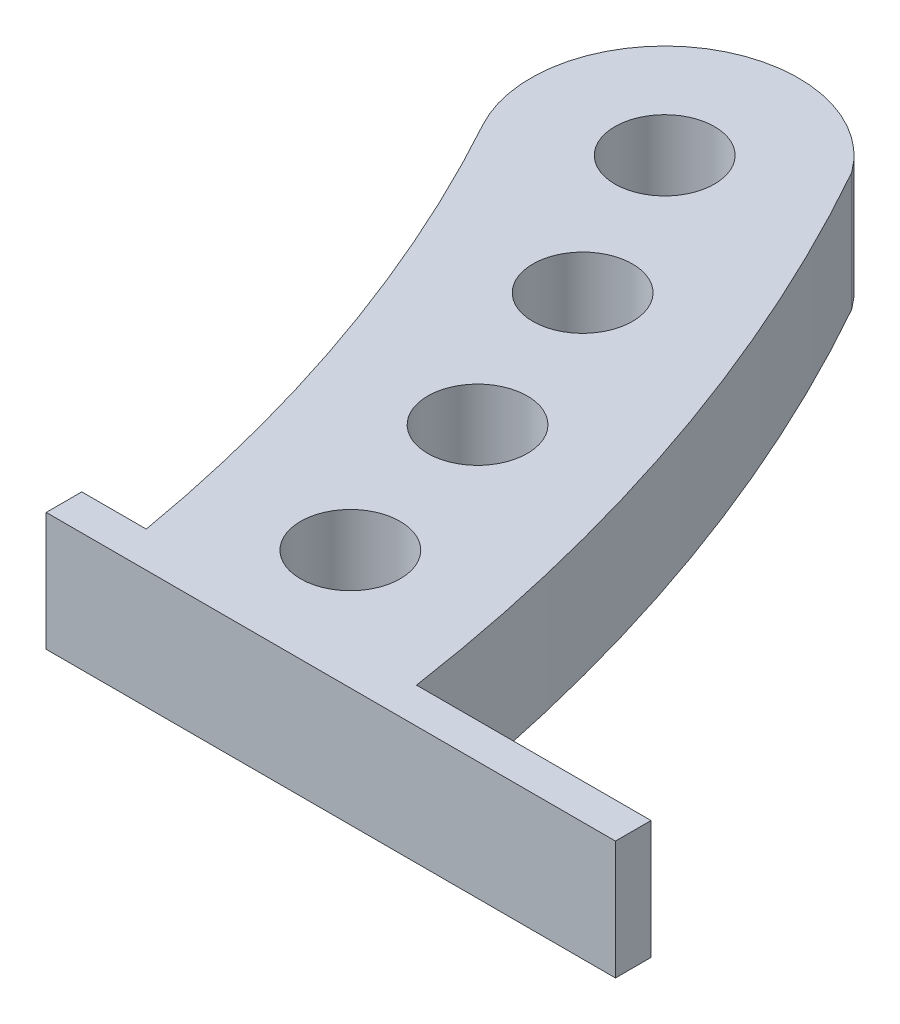
SolidWorks part; units mm, degrees
ref_plane "Front" through (0, 0, 0) normal (0, 0, 1) x (1, 0, 0)
ref_plane "Top" through (0, 0, 0) normal (0, 1, 0) x (1, 0, 0)
ref_plane "Right" through (0, 0, 0) normal (1, 0, 0) x (0, 0, -1)
sketch "Sketch1" plane through (0, 0, 0) normal (0, 1, 0) x (1, 0, 0)
  line L1 (133, 21) -> (133, 24)
  line L2 (133, 24) -> (138.435, 24)
  line L3 (161.2234, 24) -> (173, 24)
  line L4 (133, 24) -> (133, 21)
  line L5 (133, 21) -> (173, 21)
  line L7 (173, 24) -> (181, 24)
  line L8 (181, 24) -> (181, 21)
  line L9 (181, 21) -> (173, 21)
  arc A4 (138.435, 24) -> (123.1076, 67.711) centre (0, 0) ccw
  arc A5 (161.2234, 24) -> (142.1471, 79.7697) centre (0, 0) ccw
  arc A6 (136.6801, 75.176) -> (129.3199, 71.1278) centre (133, 73.1519) ccw
  arc A7 (143.4871, 77.3333) -> (123.1076, 67.711) centre (133, 73.1519) ccw
  circle A8 centre (133, 73.1519) radius 4.2
  circle A13 centre (139.5731, 59.6619) radius 4.2
  circle A14 centre (144.7821, 45.5888) radius 4.2
  circle A15 centre (148.5761, 31.0701) radius 4.2
  dimension "D1" = 4
extrude "Boss-Extrude1" add sketch "Sketch1" along normal blind 10
